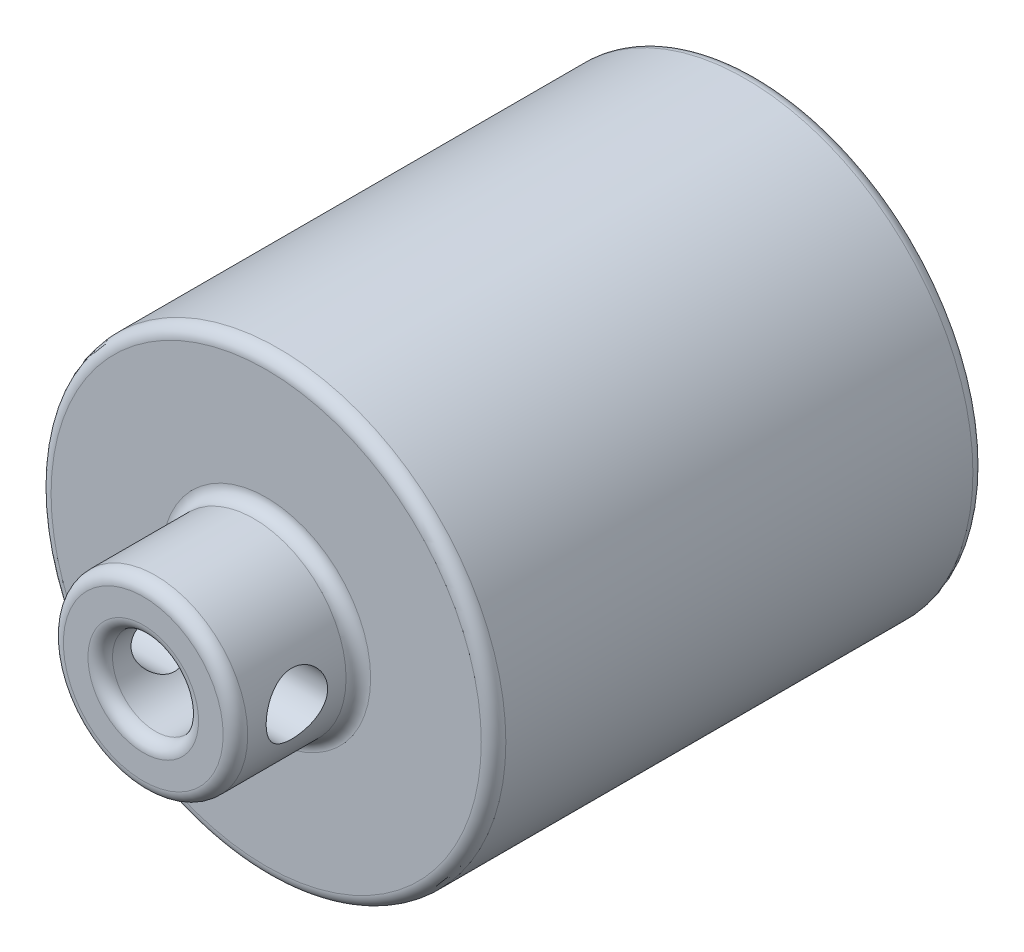
SolidWorks part; units mm, degrees
ref_plane "Front Plane" through (0, 0, 0) normal (0, 0, 1) x (1, 0, 0)
ref_plane "Top Plane" through (0, 0, 0) normal (0, 1, 0) x (1, 0, 0)
ref_plane "Right Plane" through (0, 0, 0) normal (1, 0, 0) x (0, 0, -1)
sketch "Sketch1" plane through (0, 0, 0) normal (0, 0, 1) x (1, 0, 0)
  circle A0 centre (0, 0) radius 18.5
  dimension "D1" = 37
extrude "Boss-Extrude1" add sketch "Sketch1" along normal blind 40
sketch "Sketch2" plane through (0, 0, 40) normal (0, 0, 1) x (1, 0, 0)
  circle A0 centre (0, 0) radius 7.5
  dimension "D1" = 15
extrude "Boss-Extrude2" add sketch "Sketch2" along normal blind 10
sketch "Sketch3" plane through (0, 0, 50) normal (0, 0, 1) x (1, 0, 0)
  circle A1 centre (0, 0) radius 3.5
extrude "Cut-Extrude1" cut sketch "Sketch3" against normal blind 32
fillet "Fillet1" radius 1 1 edges at (7.5, 0, 50)
fillet "Fillet2" radius 1 1 edges at (18.5, 0, 40)
fillet "Fillet3" radius 1 1 edges at (7.5, 0, 40)
fillet "Fillet4" radius 1 1 edges at (18.5, 0, 0)
fillet "Fillet6" radius 1 1 edges at (3.5, 0, 50)
sketch "Sketch4" plane through (0, 0, 0) normal (1, 0, 0) x (0, 0, -1)
  line L1 (-41, 7.5) -> (-41, -7.5) construction
  circle A0 centre (-45, 0) radius 2.5
  dimension "D1" = 5
  dimension "D2" = 4
extrude "Cut-Extrude2" cut sketch "Sketch4" against normal mid plane 282
